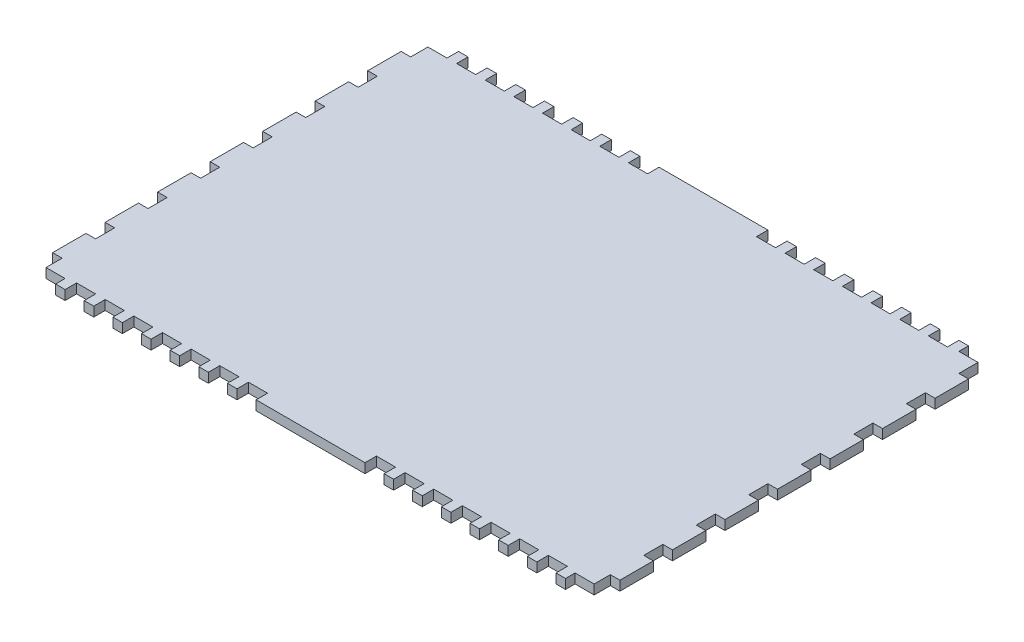
SolidWorks part; units mm, degrees
ref_plane "Plan de face" through (0, 0, 0) normal (0, 0, 1) x (1, 0, 0)
ref_plane "Plan de dessus" through (0, 0, 0) normal (0, 1, 0) x (1, 0, 0)
ref_plane "Plan de droite" through (0, 0, 0) normal (1, 0, 0) x (0, 0, -1)
sketch "Esquisse1" plane through (0, 0, 0) normal (0, 1, 0) x (1, 0, 0)
  line L1 (-38.9486, -22.0792) -> (258.0514, -22.0792)
  line L2 (-38.9486, -22.0792) -> (-38.9486, 188.8711)
  line L3 (-38.9486, 188.8711) -> (258.0514, 188.8711)
  line L4 (258.0514, -22.0792) -> (258.0514, 188.8711)
  line L5 (-38.9486, -22.0792) -> (258.0514, 188.8711) construction
  line L6 (-38.9486, 188.8711) -> (258.0514, -22.0792) construction
  point P0 (41.353, 131.8352)
extrude "Boss.-Extru.1" add sketch "Esquisse1" along normal blind 5
sketch "Esquisse2" plane through (0, 0, 0) normal (0, -1, 0) x (-1, 0, 0)
  line L1 (23.9486, -17.0792) -> (38.9486, -17.0792)
  line L2 (23.9486, -17.0792) -> (23.9486, -22.0792)
  line L3 (23.9486, -22.0792) -> (38.9486, -22.0792)
  line L4 (38.9486, -17.0792) -> (38.9486, -22.0792)
extrude "Enlèv. mat.-Extru.1" cut sketch "Esquisse2" against normal blind 10
sketch "Esquisse3" plane through (0, 0, 0) normal (0, -1, 0) x (1, 0, 0)
  line L0 (-23.9486, 22.0792) -> (258.0514, 22.0792) construction
  line L1 (-18.9486, 17.0792) -> (-8.9486, 17.0792)
  line L2 (-18.9486, 17.0792) -> (-18.9486, 22.0792)
  line L3 (-18.9486, 22.0792) -> (-8.9486, 22.0792)
  line L4 (-8.9486, 17.0792) -> (-8.9486, 22.0792)
  line L5 (-8.9486, 17.0792) -> (-8.9486, 22.0792) construction
  line L7 (-8.9486, 17.0792) -> (-18.9486, 17.0792)
  line L8 (-8.9486, 17.0792) -> (-8.9486, 16.0792)
  line L9 (-8.9486, 16.0792) -> (-18.9486, 16.0792)
  line L10 (-18.9486, 17.0792) -> (-18.9486, 16.0792)
  line M10 (258.0514, 22.0792) -> (-23.9486, 22.0792)
  dimension "D1" = 1
extrude "Enlèv. mat.-Extru.2" cut sketch "Esquisse3" against normal blind 10 contours L1 L4 L2 M10 | L8 L9 L10 L7
pattern_linear "Répétition linéaire1" count 7 spacing 15 along (1, 0, 0) of "Enlèv. mat.-Extru.2"
ref_plane "Plan1" through (109.5514, 0, 0) normal (1, 0, 0) x (0, 0, -1)
mirror "Symétrie1" about plane through (109.5514, 0, 0) normal (1, 0, 0) of "Enlèv. mat.-Extru.1", "Répétition linéaire1", "Enlèv. mat.-Extru.2"
ref_plane "Plan2" through (0, 0, -83.396) normal (0, 0, 1) x (1, 0, 0)
mirror "Symétrie2" about plane through (0, 0, -83.396) normal (0, 0, 1) of "Symétrie1", "Enlèv. mat.-Extru.1", "Répétition linéaire1", "Enlèv. mat.-Extru.2"
sketch "Esquisse4" plane through (0, 0, 0) normal (0, -1, 0) x (-1, 0, 0)
  line L0 (33.9486, 152.3297) -> (33.9486, 101.3711) construction
  line L1 (38.9486, 183.8711) -> (33.9486, 183.8711)
  line L2 (38.9486, 183.8711) -> (38.9486, 173.8711)
  line L3 (38.9486, 173.8711) -> (33.9486, 173.8711)
  line L4 (33.9486, 183.8711) -> (33.9486, 173.8711)
  dimension "D1" = 10
extrude "Enlèv. mat.-Extru.3" cut sketch "Esquisse4" against normal blind 10
pattern_linear "Répétition linéaire2" count 8 spacing 27.5 along (0, 0, 1) of "Enlèv. mat.-Extru.3"
ref_plane "Plan3" through (109.5514, 0, 0) normal (-1, 0, 0) x (0, 0, 1)
mirror "Symétrie3" about plane through (109.5514, 0, 0) normal (-1, 0, 0) of "Répétition linéaire2", "Enlèv. mat.-Extru.3"
sketch "Esquisse5" plane through (0, 0, 0) normal (0, -1, 0) x (1, 0, 0)
  line L1 (-33.9486, -183.8711) -> (-23.9486, -183.8711)
  line L2 (-33.9486, -183.8711) -> (-33.9486, -182.8711)
  line L3 (-33.9486, -182.8711) -> (-23.9486, -182.8711)
  line L4 (-23.9486, -183.8711) -> (-23.9486, -182.8711)
  dimension "D1" = 1
extrude "Enlèv. mat.-Extru.4" cut sketch "Esquisse5" against normal blind 10
